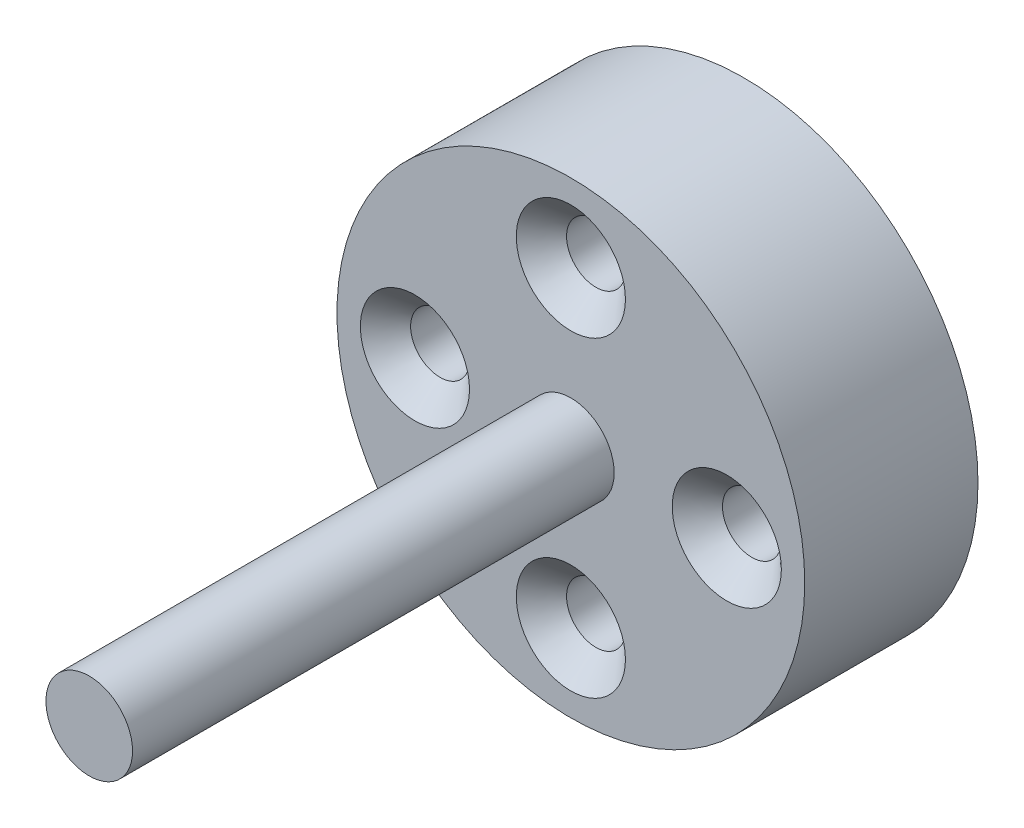
SolidWorks part; units mm, degrees
ref_plane "Front Plane" through (0, 0, 0) normal (0, 0, 1) x (1, 0, 0)
ref_plane "Top Plane" through (0, 0, 0) normal (0, 1, 0) x (1, 0, 0)
ref_plane "Right Plane" through (0, 0, 0) normal (1, 0, 0) x (0, 0, -1)
sketch "Sketch1" plane through (0, 0, 0) normal (0, 0, 1) x (1, 0, 0)
  circle A0 centre (0, 0) radius 13.5
  circle A1 centre (0, 0) radius 9
  circle A2 centre (0, 9) radius 1.6
  circle A3 centre (0, -9) radius 1.6
  circle A4 centre (-9, 0) radius 1.6
  circle A5 centre (9, 0) radius 1.6
  dimension "D1" = 27
  dimension "D2" = 18
  dimension "D3" = 3.2
  dimension "D4" = 3.2
  dimension "D5" = 3.2
  dimension "D6" = 3.2
extrude "Boss-Extrude1" add sketch "Sketch1" along normal blind 10 contours A0 A5 A1 A3 A4 A2 | A5 A1 A2 A4 A3
sketch "Sketch2" plane through (0, 0, 10) normal (0, 0, 1) x (1, 0, 0)
  circle A0 centre (0, 0) radius 2.5
  dimension "D1" = 5
extrude "Boss-Extrude2" add sketch "Sketch2" along normal blind 27.8
sketch "Sketch3" plane through (0, 0, 0) normal (0, 0, -1) x (-1, 0, 0)
  circle A0 centre (0, 0) radius 2.3
  dimension "D1" = 4.6
extrude "Cut-Extrude1" cut sketch "Sketch3" against normal blind 6
hole_wizard "CSK for M3 Flat Head Machine Screw1" positions "Sketch5" profile "Sketch6" countersink size "M3" standard "ANSI Metric"
sketch "Sketch5" plane through (0, 0, 10) normal (0, 0, 1) x (1, 0, 0)
  point P0 (0, 9)
  point P3 (9, 0)
  point P6 (-9, 0)
  point P9 (0, -9)
sketch "Sketch6" plane through (0, 9, 10) normal (1, 0, 0) x (0, -1, 0)
  line L0 (0, 0) -> (0, 11.0205)
  line L1 (0, 11.0205) -> (1.7, 9.999)
  line L2 (1.7, 9.999) -> (1.7, 1.45)
  line L3 (1.7, 1.45) -> (3.15, 0)
  line L5 (3.15, 0) -> (0, 0)
  line L6 (-1.7, 1.45) -> (-3.15, 0) construction
  line L10 (0, 11.0205) -> (-1.7, 9.999) construction
  line L11 (0, -6.35) -> (0, 107.95) construction
  dimension "Hole Dia." = 3.4
  dimension "Hole Depth" = 9.999
  dimension "Near C'Sink Dia." = 6.3
  dimension "Near C'Sink Angle" = 90
  dimension "Drill Angle" = 118
